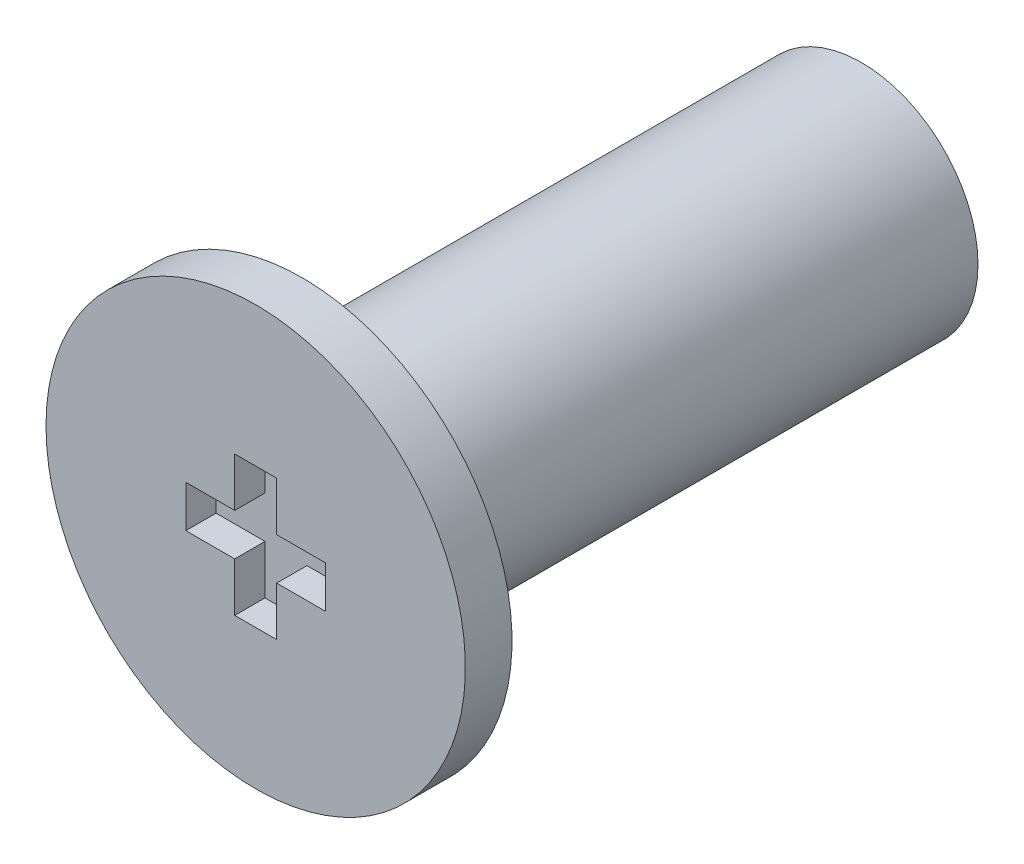
SolidWorks part; units mm, degrees
ref_plane "前视基准面" through (0, 0, 0) normal (0, 0, 1) x (1, 0, 0)
ref_plane "上视基准面" through (0, 0, 0) normal (0, 1, 0) x (1, 0, 0)
ref_plane "右视基准面" through (0, 0, 0) normal (1, 0, 0) x (0, 0, -1)
other "Configuration Table"
sketch "草图1" plane through (0, 0, 0) normal (0, 0, 1) x (1, 0, 0)
  circle A0 centre (0, 0) radius 2.5
extrude "标准杆径_头下长度" add sketch "草图1" against normal blind 12
sketch "草图2" plane through (0, 0, 0) normal (0, 0, 1) x (1, 0, 0)
  circle A0 centre (0, 0) radius 4.25
sketch "草图4" plane through (0, 0, 0) normal (0, 1, 0) x (1, 0, 0)
  line L0 (0, 0) -> (5.9, 0)
  line L1 (5.9, 0) -> (5.9, -0.3477)
  line L2 (0, -3.1) -> (0, 0)
  line L3 (0, 2) -> (0, -5.1) construction
  arc A0 (5.9, -0.3477) -> (0, -3.1) centre (0, 4.6) cw
sketch "草图5" plane through (0, 0, 0) normal (0, 0, 1) x (1, 0, 0)
  line L0 (-0.5, -2.5) -> (0.5, -2.5)
  line L1 (0.5, -2.5) -> (0.5, -0.5)
  line L2 (0.5, -0.5) -> (2.5, -0.5)
  line L3 (2.5, -0.5) -> (2.5, 0.5)
  line L4 (2.5, 0.5) -> (0.5, 0.5)
  line L5 (0.5, 0.5) -> (0.5, 2.5)
  line L6 (0.5, 2.5) -> (-0.5, 2.5)
  line L7 (-0.5, 2.5) -> (-0.5, 0.5)
  line L8 (-0.5, 0.5) -> (-2.5, 0.5)
  line L9 (-2.5, 0.5) -> (-2.5, -0.5)
  line L10 (-2.5, -0.5) -> (-0.5, -0.5)
  line L11 (-0.5, -0.5) -> (-0.5, -2.5)
sketch "草图6" plane through (0, 0, 0) normal (0, 1, 0) x (1, 0, 0)
  line L0 (0, 0) -> (4.5, 0)
  line L1 (4.5, 0) -> (4.5, -1)
  line L2 (4.5, -1) -> (0, -1)
  line L3 (0, -1) -> (0, 0)
  line L4 (0, 2) -> (0, -3) construction
revolve "已确认_十字槽超薄头" add sketch "草图6" angle 360 about L4
sketch "草图7" plane through (0, 0, 0) normal (0, 0, 1) x (1, 0, 0)
  line L0 (-0.45, -1.5) -> (0.45, -1.5)
  line L1 (0.45, -1.5) -> (0.45, -0.45)
  line L2 (0.45, -0.45) -> (1.5, -0.45)
  line L3 (1.5, -0.45) -> (1.5, 0.45)
  line L4 (1.5, 0.45) -> (0.45, 0.45)
  line L5 (0.45, 0.45) -> (0.45, 1.5)
  line L6 (0.45, 1.5) -> (-0.45, 1.5)
  line L7 (-0.45, 1.5) -> (-0.45, 0.45)
  line L8 (-0.45, 0.45) -> (-1.5, 0.45)
  line L9 (-1.5, 0.45) -> (-1.5, -0.45)
  line L10 (-1.5, -0.45) -> (-0.45, -0.45)
  line L11 (-0.45, -0.45) -> (-0.45, -1.5)
extrude "十字槽_PH2_简化" cut sketch "草图7" against normal blind 0.66 from offset 1.01
